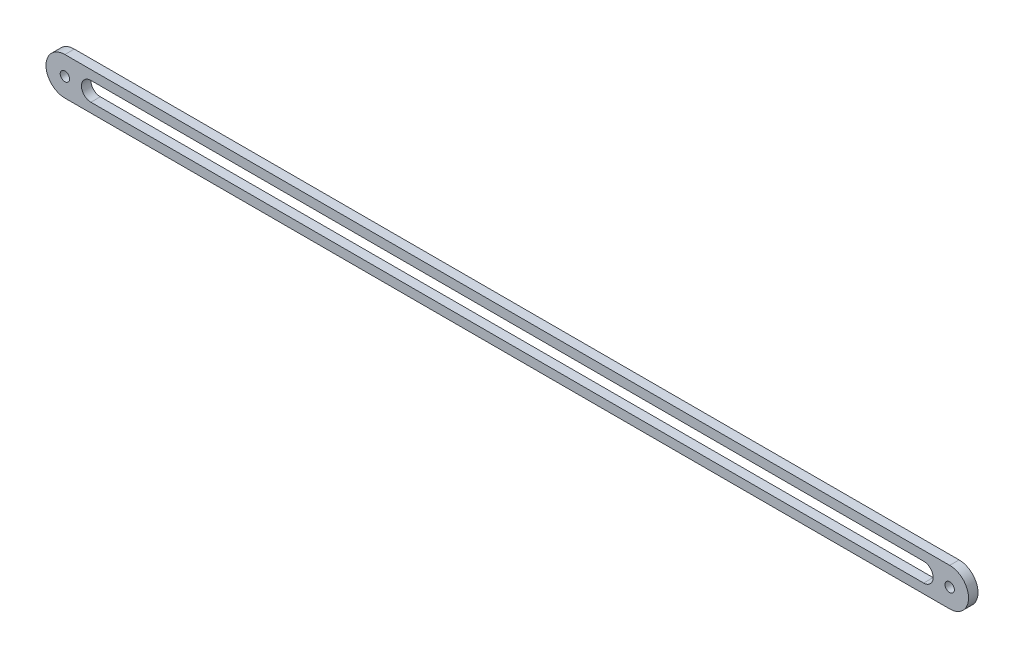
SolidWorks part; units mm, degrees
ref_plane "Front Plane" through (0, 0, 0) normal (0, 0, 1) x (1, 0, 0)
ref_plane "Top Plane" through (0, 0, 0) normal (0, 1, 0) x (1, 0, 0)
ref_plane "Right Plane" through (0, 0, 0) normal (1, 0, 0) x (0, 0, -1)
sketch "Sketch1" plane through (0, 0, 0) normal (0, 0, 1) x (1, 0, 0)
  line L0 (-150, 6.4) -> (150, 6.4)
  line L1 (150, -6.4) -> (-150, -6.4)
  line L2 (141.185, 3.2) -> (-141.185, 3.2)
  line L3 (-141.185, -3.2) -> (141.185, -3.2)
  line L4 (0, 6.4) -> (0, -6.4) construction
  circle A0 centre (-150, 0) radius 1.5875
  circle A1 centre (150, 0) radius 1.5875
  arc A2 (-150, 6.4) -> (-150, -6.4) centre (-150, 0) ccw
  arc A3 (150, -6.4) -> (150, 6.4) centre (150, 0) ccw
  arc A4 (-141.185, 3.2) -> (-141.185, -3.2) centre (-141.185, 0) ccw
  arc A5 (141.185, -3.2) -> (141.185, 3.2) centre (141.185, 0) ccw
extrude "Boss-Extrude2" add sketch "Sketch1" along normal mid plane 3.2
